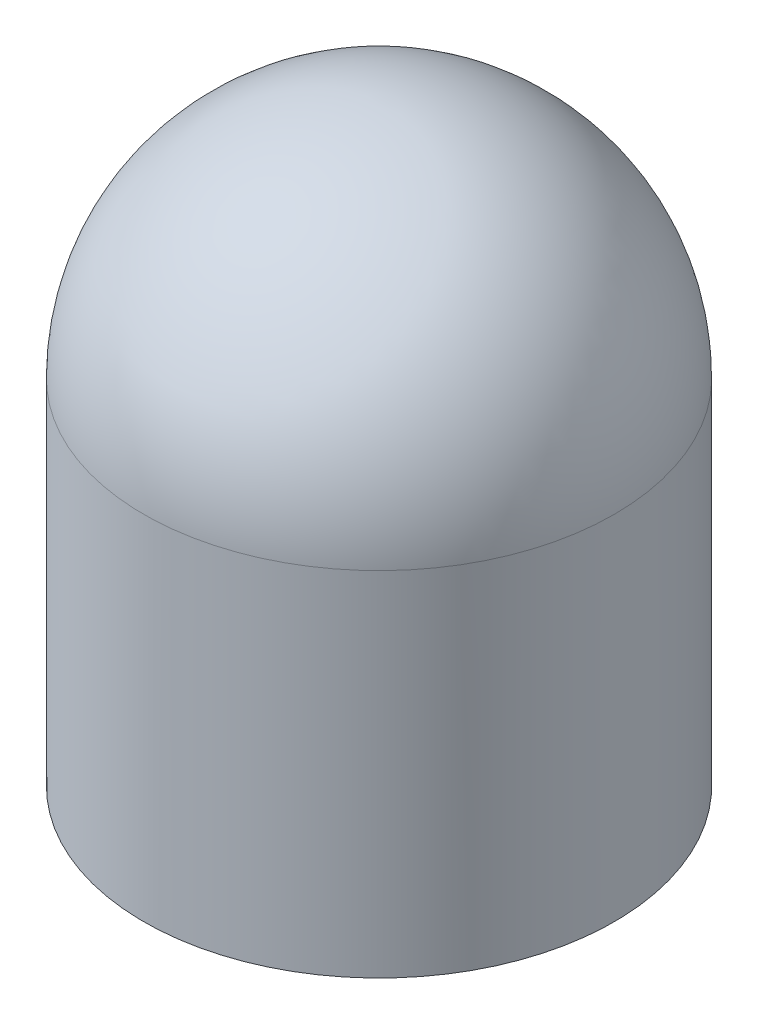
SolidWorks part; units mm, degrees
material "ABS"
ref_plane "Plan de face" through (0, 0, 0) normal (0, 0, 1) x (1, 0, 0)
ref_plane "Plan de dessus" through (0, 0, 0) normal (0, 1, 0) x (1, 0, 0)
ref_plane "Plan de droite" through (0, 0, 0) normal (1, 0, 0) x (0, 0, -1)
sketch "Esquisse2" plane through (0, 0, 0) normal (0, 0, 1) x (1, 0, 0)
  line L0 (-4, 0) -> (-1.8846, 0) construction
  line L1 (-1.5, -3) -> (-1.5, -6)
  line L2 (-1.5, -3) -> (0, -3)
  line L3 (0, -3) -> (0, 4)
  line L4 (-4, 0) -> (0, 0) construction
  line L5 (0, 0) -> (4, 0) construction
  line L6 (0, 4) -> (0, 0) construction
  line L7 (-1.5, -1.5) -> (0, -1.5) construction
  line L8 (0, -1.5) -> (1.5, -1.5) construction
  line L9 (-1.5, -3) -> (-3.9639, -0.5361) construction
  line L10 (-4, 0) -> (-4, -6)
  line L11 (-4, -6) -> (-1.5, -6)
  arc A0 (-4, 0) -> (0, 4) centre (0, 0) cw
  dimension "D1" = 3
  dimension "D2" = 8
  dimension "D3" = 3
  dimension "D4" = 135
  dimension "D5" = 6
  dimension "D6" = 1.5
revolve "Révolution2" add sketch "Esquisse2" angle 360 about L6
sketch "Esquisse4" [suppressed] plane through (0, 0, 0) normal (0, -1, 0) x (-1, 0, 0)
  circle A0 centre (0, 0) radius 2.525
  circle A1 centre (0, 0) radius 12.525
  circle A2 centre (0, 0) radius 1.525 construction
  dimension "D1" = 1
  dimension "D2" = 10
extrude "Enlèv. mat.-Extru.2" [suppressed] cut sketch "Esquisse4" against normal blind 10
sketch "Esquisse3" plane through (0, -6, 0) normal (0, -1, 0) x (1, 0, 0)
  text T0 "<b>0</b>" font "Century Gothic" height in points 6
extrude "Enlèv. mat.-Extru.1" cut sketch "Esquisse3" against normal blind 1
fillet "Congé1" [suppressed] radius 2
equation "\"plug_DI\"= 1.5mm'size of the inner extrude of the plug (finger contact)"
equation "\"magnet_DI\"= 3mm'inner diameter of the o-ring magnet"
equation "\"magnet_DE\"= 8mm'external diameter of the o-ring magnet"
equation "\"magnet_H\"= 3mm'tall of the magnet"
equation "\"gap_magnet_H\"= 1mm'gap between the 2 magnets"
